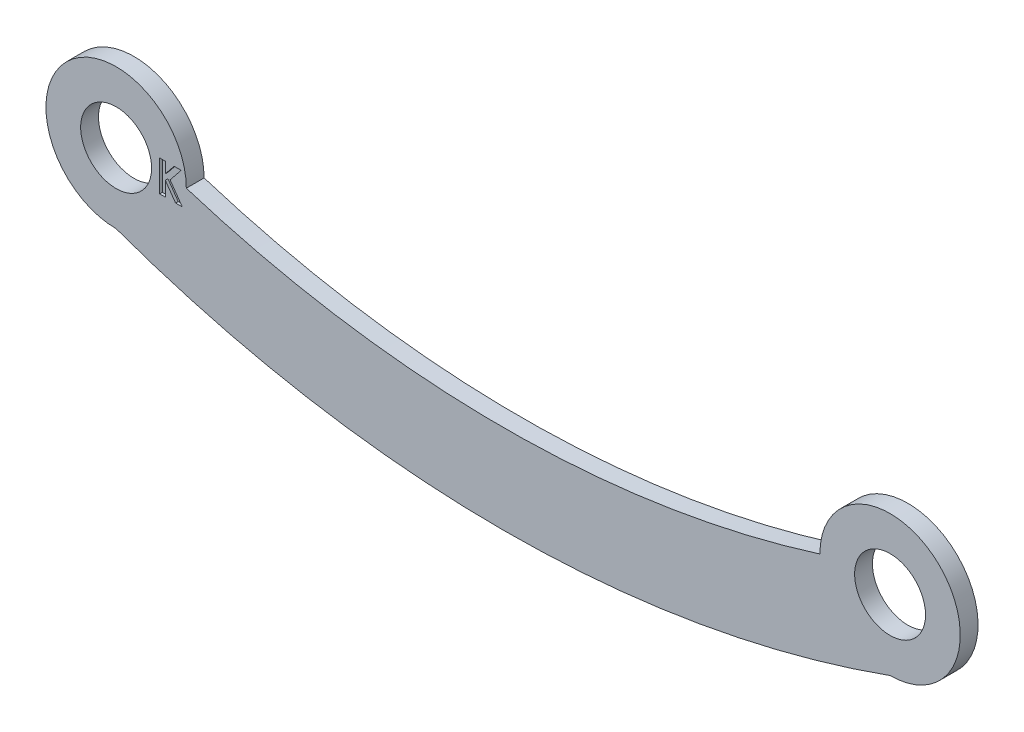
SolidWorks part; units mm, degrees
ref_plane "Plan de face" through (0, 0, 0) normal (1, 0, 0) x (0, 1, 0)
ref_plane "Plan de dessus" through (0, 0, 0) normal (0, 0, 1) x (0, 1, 0)
ref_plane "Plan de droite" through (0, 0, 0) normal (0, 1, 0) x (-1, 0, 0)
sketch "Esquisse1" plane through (0, 0, 0) normal (0, 0, 1) x (0, 1, 0)
  line L0 (0, 0) -> (0, 87) construction
  circle A0 centre (0, 87) radius 3.985
  circle A1 centre (0, 0) radius 3.985
  circle A2 centre (0, 87) radius 7.89
  circle A3 centre (0, 0) radius 7.89
  arc A4 (-7.89, 0) -> (-7.89, 87) centre (113.0021, 43.5) cw
  arc A5 (0, 7.89) -> (0, 79.11) centre (113.0021, 43.5) cw
  arc A6 (1.5194, 3.3857) -> (1.5194, 83.6143) centre (113.0021, 43.5) cw construction
  dimension "D2" = 7.97
  dimension "D3" = 15.78
  dimension "D4" = 10
  dimension "D1" = 87
extrude "Boss.-Extru.1" add sketch "Esquisse1" along normal blind 2
sketch "Esquisse2" plane through (0, 0, 2) normal (0, 0, 1) x (1, 0, 0)
  text T0 "<b>K</b>"
extrude "Enlèv. mat.-Extru.1" cut sketch "Esquisse2" against normal blind 0.3
